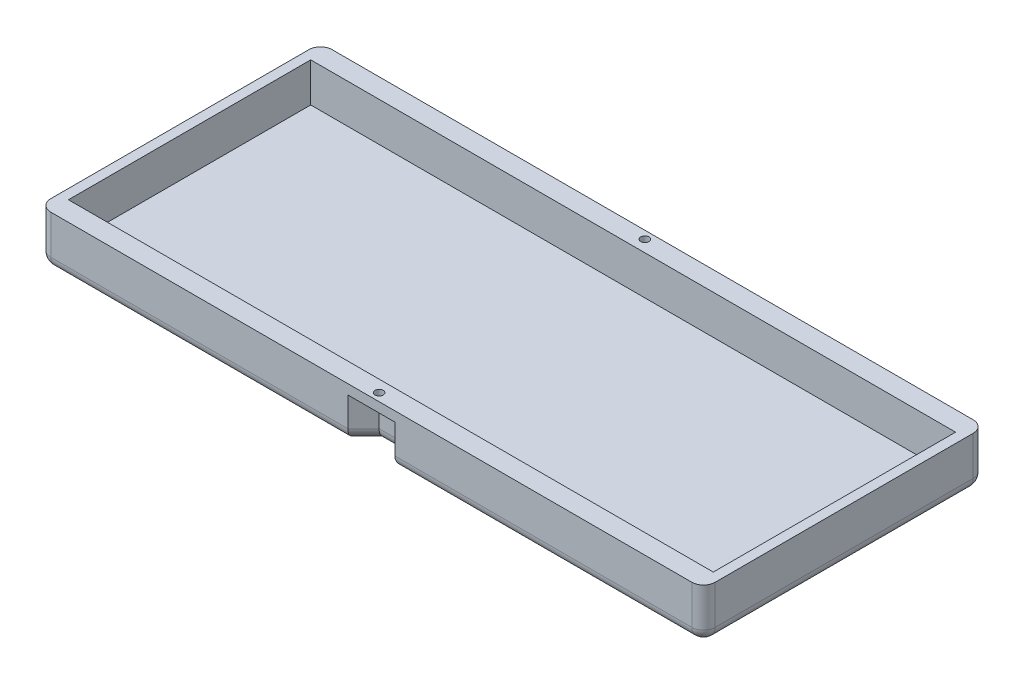
SolidWorks part; units mm, degrees
ref_plane "前视基准面" through (0, 0, 0) normal (0, 0, 1) x (1, 0, 0)
ref_plane "上视基准面" through (0, 0, 0) normal (0, 1, 0) x (1, 0, 0)
ref_plane "右视基准面" through (0, 0, 0) normal (1, 0, 0) x (0, 0, -1)
other "Configuration Table"
sketch "草图1" plane through (0, 0, 0) normal (0, 1, 0) x (1, 0, 0)
  line L1 (-85, -36) -> (85, -36)
  line L2 (-85, -36) -> (-85, 36)
  line L3 (-85, 36) -> (85, 36)
  line L4 (85, -36) -> (85, 36)
  line L5 (-85, -36) -> (85, 36) construction
  line L6 (-85, 36) -> (85, -36) construction
  point P0 (0, 0)
  dimension "D1" = 170
  dimension "D2" = 72
extrude "凸台-拉伸1" add sketch "草图1" along normal blind 3
sketch "草图2" plane through (0, 3, 0) normal (0, 1, 0) x (1, 0, 0)
  line L4 (85, -36) -> (85, 36)
  line L5 (85, 36) -> (-85, 36)
  line L6 (-85, 36) -> (-85, -36)
  line L7 (-85, -36) -> (85, -36)
  line L8 (85, -36) -> (85, 36)
  line L9 (85, 36) -> (-85, 36)
  line L10 (-85, 36) -> (-85, -36)
  line L11 (-85, -36) -> (85, -36)
  line L13 (-82.5, -31) -> (82.5, -31)
  line L14 (-82.5, -31) -> (-82.5, 31)
  line L15 (-82.5, 31) -> (82.5, 31)
  line L16 (82.5, -31) -> (82.5, 31)
  line L17 (-82.5, -31) -> (82.5, 31) construction
  line L18 (-82.5, 31) -> (82.5, -31) construction
  point P2 (0, 0)
  point P9 (-82.5, 0)
  dimension "D2" = 5
  dimension "D3" = 5
  dimension "D4" = 2.5
  dimension "D1" = 0
extrude "凸台-拉伸2" add sketch "草图2" along normal blind 10
sketch "草图3" plane through (0, 0, 0) normal (0, -1, 0) x (1, 0, 0)
  line L1 (-85, 36) -> (85, 36) construction
  line L3 (-6, 36) -> (-2, 32)
  line L4 (-2, 32) -> (2, 32)
  line L5 (2, 32) -> (6, 36)
  line L6 (6, 36) -> (-6, 36)
  line L7 (-12.3606, 0) -> (13.3841, 0) construction
  line L8 (6, -36) -> (-6, -36)
  line L9 (2, -32) -> (6, -36)
  line L10 (-2, -32) -> (2, -32)
  line L11 (-6, -36) -> (-2, -32)
  dimension "D1" = 4
  dimension "D2" = 135
  dimension "D3" = 135
extrude "切除-拉伸1" cut sketch "草图3" against normal blind 10.5
sketch "草图5" plane through (0, 10.5, 0) normal (0, -1, 0) x (1, 0, 0)
  line L0 (0, 36) -> (0, 32) construction
  line L1 (6, 36) -> (-6, 36) construction
  line L2 (-2, 32) -> (2, 32) construction
  circle A0 centre (0, 34) radius 1.05
  dimension "D1" = 2.1
extrude "切除-拉伸2" cut sketch "草图5" against normal blind 10.5
sketch "草图6" plane through (0, 10.5, 0) normal (0, -1, 0) x (1, 0, 0)
  line L0 (0, -36) -> (0, -32) construction
  line L1 (-6, -36) -> (6, -36) construction
  line L2 (2, -32) -> (-2, -32) construction
  circle A0 centre (0, -34) radius 1.05
  dimension "D1" = 2.1
extrude "切除-拉伸3" cut sketch "草图6" against normal blind 10.5
fillet "圆角1" radius 3 16 edges at (85, 6.5, 36) (85, 6.5, -36) (45.5, 0, 36) (85, 0, 0) (45.5, 0, -36) (4, 0, -34) (0, 0, -32) (-4, 0, -34) (-45.5, 0, -36) (-85, 0, 0) (-45.5, 0, 36) (-4, 0, 34) (0, 0, 32) (4, 0, 34) (-85, 6.5, -36) (-85, 6.5, 36)
